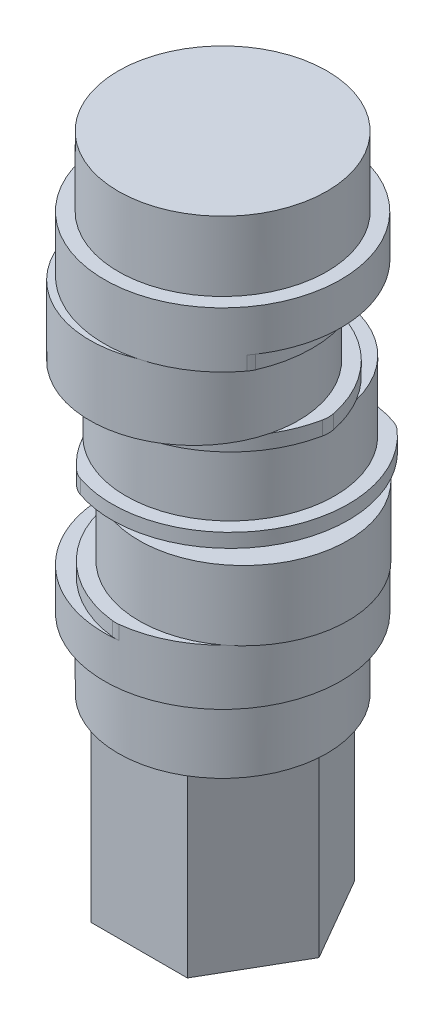
SolidWorks part; units mm, degrees
ref_plane "Front Plane" through (0, 0, 0) normal (0, 0, 1) x (1, 0, 0)
ref_plane "Top Plane" through (0, 0, 0) normal (0, 1, 0) x (1, 0, 0)
ref_plane "Right Plane" through (0, 0, 0) normal (1, 0, 0) x (0, 0, -1)
sketch "Sketch3" plane through (0, 0, 0) normal (0, 1, 0) x (1, 0, 0)
  line L0 (-0.75, 1.299) -> (0, 0) construction
  line L1 (0, 0) -> (-0.75, -1.299) construction
  line L2 (0, 0) -> (1.5, 0) construction
  circle A0 centre (0, 0) radius 1.5 construction
  circle A1 centre (1.5, 0) radius 8.5
  circle A2 centre (-0.75, 1.299) radius 8.5
  circle A3 centre (-0.75, -1.299) radius 8.5
  dimension "D1" = 3
  dimension "D2" = 17
  dimension "D3" = 120
  dimension "D4" = 120
sketch "Sketch4" plane through (0, 0, 0) normal (0, 1, 0) x (1, 0, 0)
  line L1 (-3.4641, 6) -> (-6.9282, 0)
  line L2 (-6.9282, 0) -> (-3.4641, -6)
  line L3 (-3.4641, -6) -> (3.4641, -6)
  line L4 (3.4641, -6) -> (6.9282, 0)
  line L5 (6.9282, 0) -> (3.4641, 6)
  line L6 (3.4641, 6) -> (-3.4641, 6)
  circle A0 centre (0, 0) radius 6 construction
  dimension "D1" = 12
extrude "Boss-Extrude1" add sketch "Sketch4" along normal blind 13
sketch "Sketch5" plane through (0, 13, 0) normal (0, 1, 0) x (1, 0, 0)
  circle A0 centre (0, 0) radius 7.5
  dimension "D1" = 15
extrude "Boss-Extrude2" add sketch "Sketch5" along normal blind 8
sketch "Sketch6" plane through (0, 21, 0) normal (0, 1, 0) x (1, 0, 0)
  circle A0 centre (0, 0) radius 8.5
  circle A1 centre (1.5, 0) radius 8.5
  circle M1 centre (0, 0) radius 7.5
  dimension "D1" = 17
extrude "Boss-Extrude3" add sketch "Sketch6" along normal blind 1 contours A1 M1 | A0 A1 M1
sketch "Sketch7" plane through (0, 22, 0) normal (0, 1, 0) x (1, 0, 0)
  circle A0 centre (1.5, 0) radius 7.5
  arc A1 (-4.5833, 5.9366) -> (-4.5833, -5.9366) centre (0, 0) ccw construction
extrude "Boss-Extrude4" add sketch "Sketch7" along normal blind 5
sketch "Sketch8" plane through (0, 27, 0) normal (0, 1, 0) x (1, 0, 0)
  circle A0 centre (1.5, 0) radius 8.5
  circle A1 centre (-0.75, 1.299) radius 8.5
  circle A2 centre (1.5, 0) radius 8.5 construction
  circle M1 centre (1.5, 0) radius 7.5
extrude "Boss-Extrude5" add sketch "Sketch8" along normal blind 1 contours A1 M1 | A1 A0 M1
sketch "Sketch9" plane through (0, 28, 0) normal (0, 1, 0) x (1, 0, 0)
  circle A0 centre (-0.75, 1.299) radius 7.5
  arc A1 (-0.6012, -7.1997) -> (6.6845, 5.4195) centre (1.5, 0) ccw construction
extrude "Boss-Extrude6" add sketch "Sketch9" along normal blind 5
sketch "Sketch11" plane through (0, 33, 0) normal (0, 1, 0) x (1, 0, 0)
  circle A0 centre (-0.75, 1.299) radius 8.5
  circle A1 centre (-0.75, -1.299) radius 8.5
  arc A2 (-3.8251, -6.6252) -> (4.5751, 7.9243) centre (-0.75, 1.299) ccw construction
  circle M1 centre (-0.75, 1.299) radius 7.5
extrude "Boss-Extrude7" add sketch "Sketch11" along normal blind 1 contours A1 M1 | A0 A1 M1
sketch "Sketch12" plane through (0, 34, 0) normal (0, 1, 0) x (1, 0, 0)
  circle A0 centre (-0.75, -1.299) radius 7.5
  arc A1 (6.5357, 3.0792) -> (-8.0357, 3.0792) centre (-0.75, 1.299) ccw construction
extrude "Boss-Extrude8" add sketch "Sketch12" along normal blind 5
sketch "Sketch13" plane through (0, 39, 0) normal (0, 1, 0) x (1, 0, 0)
  circle A0 centre (-0.75, -1.299) radius 8.5
  circle A1 centre (0, 0) radius 8.5
  arc A3 (7.6501, 0) -> (-9.1501, 0) centre (-0.75, -1.299) ccw construction
  circle M1 centre (-0.75, -1.299) radius 7.5
extrude "Boss-Extrude9" add sketch "Sketch13" along normal blind 1 contours A1 M1 | A1 A0 M1
sketch "Sketch14" plane through (0, 40, 0) normal (0, 1, 0) x (1, 0, 0)
  circle A0 centre (0, 0) radius 7.5
  arc A1 (6.5357, 3.0792) -> (-8.0357, 3.0792) centre (-0.75, 1.299) ccw construction
extrude "Boss-Extrude10" add sketch "Sketch14" along normal blind 8
fillet "Fillet1" radius 2 8 edges at (0.75, 21.5, 8.4668) (0.75, 21.5, -8.4668) (4.5751, 27.5, -7.9243) (-3.8251, 27.5, 6.6252) (-9.1501, 33.5, 0) (7.6501, 33.5, 0) (6.9575, 39.5, 4.8829) (-7.7075, 39.5, -3.5839)
sketch "Sketch15" plane through (0, 21, 0) normal (0, -1, 0) x (1, 0, 0)
  circle A0 centre (0, 0) radius 8.5
  dimension "D1" = 17
extrude "Boss-Extrude11" add sketch "Sketch15" along normal blind 3
sketch "Sketch16" plane through (0, 40, 0) normal (0, -1, 0) x (1, 0, 0)
  circle A0 centre (0, 0) radius 8.5
  dimension "D1" = 17
extrude "Boss-Extrude12" add sketch "Sketch16" against normal blind 3
equation "\"N_pin\"= 24"
equation "\"R_pin\"= 60"
equation "\"d_pin\"= 13"
equation "\"e\"= 1.5"
equation "\"t_disk\"= 5"
equation "\"N_outpin\"= 8"
equation "\"R_outpin\"= 34"
equation "\"d_outpin\"= 13"
equation "\"N_lobes\"= \"N_pin\" - 1"
equation "\"d_outhole\"= \"d_outpin\" + 2 * \"e\""
equation "\"ratio\"= \"N_lobes\""
equation "\"d_center\"= 24"
equation "\"a_hole1\"= 0 / \"N_lobes\""
equation "\"a_hole2\"= 360 / \"N_disk\" / \"N_lobes\""
equation "\"a_hole3\"= 720 / \"N_disk\" / \"N_lobes\""
equation "\"N_disk\"= 3"
equation "\"t_gap\"= 1"
equation "\"L_stack\"= \"N_disk\" * \"t_disk\" + (\"N_disk\" - 1) * \"t_gap\""
equation "\"d_pinshaft\"= 6"
equation "\"d_ecc\"= 15"
equation "\"d_outbrg\"= 47"
equation "\"w_outbrg\"= 7"
equation "\"d_outshaft\"= 35"
equation "\"w_brg\"= 5"
equation "\"D1@Boss-Extrude5\"=\"t_gap\""
equation "\"D1@Boss-Extrude7\"=\"t_gap\""
equation "\"c_run\"= 0.5"
equation "\"c_ax\"= \"t_gap\""
equation "\"D_pocket\"= 2 * \"R_pin\" + \"d_pin\" + 2 * \"c_run\""
equation "\"h_pocket\"= \"L_stack\" + 2 * \"c_ax\""
equation "\"t_floor\"= 8"
equation "\"d_insert\"= 5.6"
equation "\"N_bolt\"= 8"
equation "\"R_bolt\"= \"D_pocket\" / 2 + 2 + \"d_insert\" / 2"
equation "\"D_housing\"= 2 * (\"R_bolt\" + \"d_insert\" / 2 + 2.5)"
equation "\"D1@Boss-Extrude2\"=\"t_floor\""
equation "\"D1@Sketch5\"=\"d_ecc\""
equation "\"D1@Boss-Extrude10\"=\"t_floor\""
equation "\"D1@Boss-Extrude8\"=\"w_brg\""
equation "\"D1@Boss-Extrude6\"=\"w_brg\""
equation "\"D1@Boss-Extrude4\"=\"w_brg\""
equation "\"D1@Sketch6\"=\"d_ecc\"+2"
equation "\"D1@Sketch15\"=\"d_ecc\"+2"
equation "\"D1@Boss-Extrude11\"=\"t_floor\"-\"w_brg\""
equation "\"D1@Boss-Extrude3\"=\"t_gap\""
equation "\"D1@Boss-Extrude9\"=\"t_gap\""
equation "\"D1@Sketch16\"=\"d_ecc\"+2"
equation "\"D1@Boss-Extrude12\"=\"t_floor\"-\"w_brg\""
